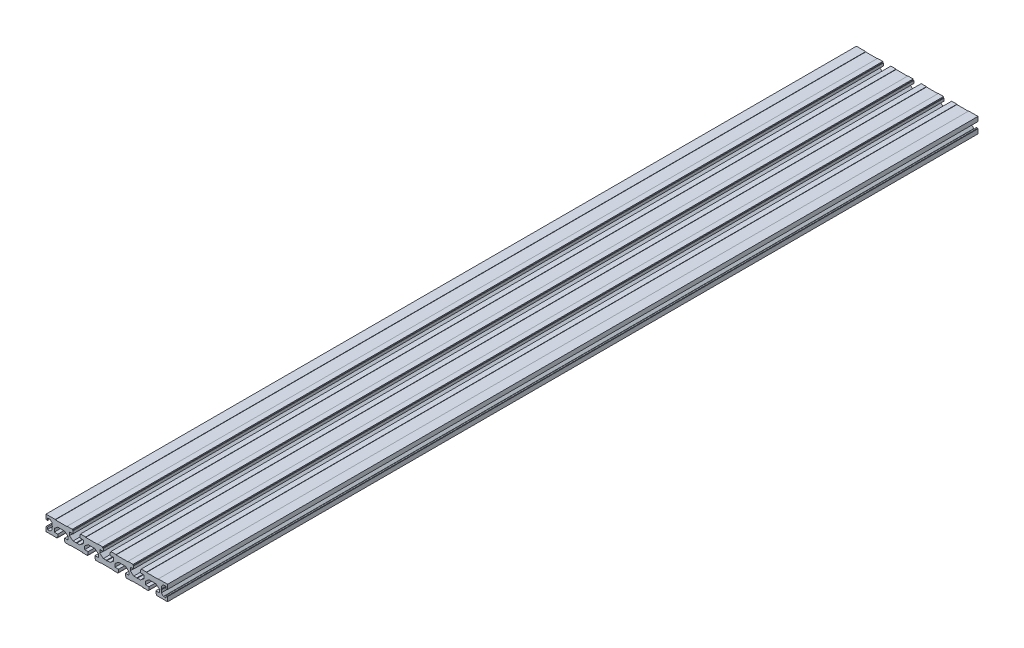
SolidWorks part; units mm, degrees
ref_plane "Front Plane" through (0, 0, 0) normal (0, 0, 1) x (1, 0, 0)
ref_plane "Top Plane" through (0, 0, 0) normal (0, 1, 0) x (1, 0, 0)
ref_plane "Right Plane" through (0, 0, 0) normal (1, 0, 0) x (0, 0, -1)
sketch "Model" plane through (0, 0, 0) normal (0, 0, 1) x (1, 0, 0)
  line L0 (-16.5, -11.25) -> (-16.5, -9.75)
  line L1 (-16.5, -9.75) -> (-17.4, -9.75)
  line L2 (-17.4, -9.75) -> (-17.4, -5.75)
  line L3 (-17.4, -5.75) -> (-12.25, -5.75)
  line L4 (-12.25, -5.75) -> (-12.25, -0.9799)
  line L5 (-12.25, -0.9799) -> (-17.5, 3.25)
  line L6 (-17.5, 3.25) -> (-22, 3.25)
  line L7 (-22, 3.25) -> (-22.5, 3.75)
  line L8 (-22.5, 3.75) -> (-23, 3.25)
  line L9 (-23, 3.25) -> (-27.5, 3.25)
  line L10 (-27.5, 3.25) -> (-32.75, -0.9799)
  line L11 (-32.75, -0.9799) -> (-32.75, -5.75)
  line L12 (-32.75, -5.75) -> (-27.6, -5.75)
  line L13 (-27.6, -5.75) -> (-27.6, -9.75)
  line L14 (-27.6, -9.75) -> (-28.5, -9.75)
  line L15 (-28.5, -11.25) -> (-28.5, -9.75)
  line L16 (-36.25, -11.25) -> (-36.25, -10.75)
  line L17 (-36.25, -10.75) -> (-53.75, -10.75)
  line L18 (-53.75, -11.25) -> (-53.75, -10.75)
  line L19 (-61.5, -11.25) -> (-61.5, -9.75)
  line L20 (-61.5, -9.75) -> (-62.4, -9.75)
  line L21 (-62.4, -9.75) -> (-62.4, -5.75)
  line L22 (-62.4, -5.75) -> (-57.25, -5.75)
  line L23 (-57.25, -5.75) -> (-57.25, -0.9799)
  line L24 (-57.25, -0.9799) -> (-62.5, 3.25)
  line L25 (-62.5, 3.25) -> (-67, 3.25)
  line L26 (-67, 3.25) -> (-67.5, 3.75)
  line L27 (-67.5, 3.75) -> (-68, 3.25)
  line L28 (-68, 3.25) -> (-72.5, 3.25)
  line L29 (-72.5, 3.25) -> (-77.75, -0.9799)
  line L30 (-77.75, -0.9799) -> (-77.75, -5.75)
  line L31 (-77.75, -5.75) -> (-72.6, -5.75)
  line L32 (-72.6, -5.75) -> (-72.6, -9.75)
  line L33 (-72.6, -9.75) -> (-73.5, -9.75)
  line L34 (-73.5, -11.25) -> (-73.5, -9.75)
  line L35 (-90, -4.6) -> (-89.5, -4.1)
  line L36 (-89.5, -4.1) -> (-87.8, -4.1)
  line L37 (-87.8, -4.1) -> (-87.8, -7.456)
  line L38 (-87.8, -7.456) -> (-83.8702, -7.456)
  line L39 (-83.8702, -7.456) -> (-80.75, -4.3358)
  line L40 (-80.75, -4.3358) -> (-80.75, -0.5)
  line L41 (-80.75, -0.5) -> (-80.25, 0)
  line L42 (-80.25, 0) -> (-80.75, 0.5)
  line L43 (-80.75, 0.5) -> (-80.75, 4.3358)
  line L44 (-80.75, 4.3358) -> (-83.8702, 7.456)
  line L45 (-83.8702, 7.456) -> (-87.8, 7.456)
  line L46 (-87.8, 7.456) -> (-87.8, 4.1)
  line L47 (-87.8, 4.1) -> (-89.5, 4.1)
  line L48 (-76.25, 11.25) -> (-90, 11.25)
  line L49 (-76.25, 11.25) -> (-76.25, 10.75)
  line L50 (-76.25, 10.75) -> (-58.75, 10.75)
  line L51 (-58.75, 11.25) -> (-58.75, 10.75)
  line L52 (-51, 11.25) -> (-58.75, 11.25)
  line L53 (-51, 11.25) -> (-51, 9.75)
  line L54 (-51, 9.75) -> (-50.1, 9.75)
  line L55 (-50.1, 9.75) -> (-50.1, 5.75)
  line L56 (-50.1, 5.75) -> (-55.25, 5.75)
  line L57 (-55.25, 5.75) -> (-55.25, 0.9799)
  line L58 (-55.25, 0.9799) -> (-50, -3.25)
  line L59 (-50, -3.25) -> (-45.5, -3.25)
  line L60 (-45.5, -3.25) -> (-45, -3.75)
  line L61 (-45, -3.75) -> (-44.5, -3.25)
  line L62 (-44.5, -3.25) -> (-40, -3.25)
  line L63 (-40, -3.25) -> (-34.75, 0.9799)
  line L64 (-34.75, 0.9799) -> (-34.75, 5.75)
  line L65 (-34.75, 5.75) -> (-39.9, 5.75)
  line L66 (-39.9, 5.75) -> (-39.9, 9.75)
  line L67 (-39.9, 9.75) -> (-39, 9.75)
  line L68 (-39, 11.25) -> (-39, 9.75)
  line L69 (-31.25, 11.25) -> (-39, 11.25)
  line L70 (-31.25, 11.25) -> (-31.25, 10.75)
  line L71 (-31.25, 10.75) -> (-13.75, 10.75)
  line L72 (-13.75, 11.25) -> (-13.75, 10.75)
  line L73 (-6, 11.25) -> (-13.75, 11.25)
  line L74 (-6, 11.25) -> (-6, 9.75)
  line L75 (-6, 9.75) -> (-5.1, 9.75)
  line L76 (-5.1, 9.75) -> (-5.1, 5.75)
  line L77 (-5.1, 5.75) -> (-10.25, 5.75)
  line L78 (-10.25, 5.75) -> (-10.25, 0.9799)
  line L79 (-10.25, 0.9799) -> (-5, -3.25)
  line L80 (-5, -3.25) -> (-0.5, -3.25)
  line L81 (-0.5, -3.25) -> (0, -3.75)
  line L82 (0, -3.75) -> (0.5, -3.25)
  line L83 (0.5, -3.25) -> (5, -3.25)
  line L84 (5, -3.25) -> (10.25, 0.9799)
  line L85 (10.25, 0.9799) -> (10.25, 5.75)
  line L86 (10.25, 5.75) -> (5.1, 5.75)
  line L87 (5.1, 5.75) -> (5.1, 9.75)
  line L88 (5.1, 9.75) -> (6, 9.75)
  line L89 (6, 11.25) -> (6, 9.75)
  line L90 (13.75, 11.25) -> (6, 11.25)
  line L91 (13.75, 11.25) -> (13.75, 10.75)
  line L92 (13.75, 10.75) -> (31.25, 10.75)
  line L93 (31.25, 11.25) -> (31.25, 10.75)
  line L94 (39, 11.25) -> (31.25, 11.25)
  line L95 (39, 9.75) -> (39.9, 9.75)
  line L96 (39.9, 9.75) -> (39.9, 5.75)
  line L97 (39.9, 5.75) -> (34.75, 5.75)
  line L98 (34.75, 5.75) -> (34.75, 0.9799)
  line L99 (34.75, 0.9799) -> (40, -3.25)
  line L100 (40, -3.25) -> (44.5, -3.25)
  line L101 (44.5, -3.25) -> (45, -3.75)
  line L102 (45, -3.75) -> (45.5, -3.25)
  line L103 (45.5, -3.25) -> (50, -3.25)
  line L104 (50, -3.25) -> (55.25, 0.9799)
  line L105 (55.25, 0.9799) -> (55.25, 5.75)
  line L106 (55.25, 5.75) -> (50.1, 5.75)
  line L107 (50.1, 5.75) -> (50.1, 9.75)
  line L108 (50.1, 9.75) -> (51, 9.75)
  line L109 (51, 11.25) -> (51, 9.75)
  line L110 (58.75, 11.25) -> (51, 11.25)
  line L111 (58.75, 11.25) -> (58.75, 10.75)
  line L112 (58.75, 10.75) -> (76.25, 10.75)
  line L113 (76.25, 11.25) -> (76.25, 10.75)
  line L114 (90, 11.25) -> (76.25, 11.25)
  line L115 (90, 4.6) -> (90, 11.25)
  line L116 (90, 4.6) -> (89.5, 4.1)
  line L117 (89.5, 4.1) -> (87.8, 4.1)
  line L118 (87.8, 4.1) -> (87.8, 7.456)
  line L119 (87.8, 7.456) -> (83.8702, 7.456)
  line L120 (83.8702, 7.456) -> (80.75, 4.3358)
  line L121 (80.75, 4.3358) -> (80.75, 0.5)
  line L122 (80.75, 0.5) -> (80.25, 0)
  line L123 (80.25, 0) -> (80.75, -0.5)
  line L124 (80.75, -0.5) -> (80.75, -4.3358)
  line L125 (80.75, -4.3358) -> (83.8702, -7.456)
  line L126 (83.8702, -7.456) -> (87.8, -7.456)
  line L127 (87.8, -7.456) -> (87.8, -4.1)
  line L128 (87.8, -4.1) -> (89.5, -4.1)
  line L129 (89.5, -4.1) -> (90, -4.6)
  line L130 (90, -11.25) -> (90, -4.6)
  line L131 (73.5, -11.25) -> (73.5, -9.75)
  line L132 (73.5, -9.75) -> (72.6, -9.75)
  line L133 (72.6, -9.75) -> (72.6, -5.75)
  line L134 (72.6, -5.75) -> (77.75, -5.75)
  line L135 (77.75, -5.75) -> (77.75, -0.9799)
  line L136 (77.75, -0.9799) -> (72.5, 3.25)
  line L137 (72.5, 3.25) -> (68, 3.25)
  line L138 (68, 3.25) -> (67.5, 3.75)
  line L139 (67.5, 3.75) -> (67, 3.25)
  line L140 (67, 3.25) -> (62.5, 3.25)
  line L141 (62.5, 3.25) -> (57.25, -0.9799)
  line L142 (57.25, -0.9799) -> (57.25, -5.75)
  line L143 (57.25, -5.75) -> (62.4, -5.75)
  line L144 (62.4, -5.75) -> (62.4, -9.75)
  line L145 (62.4, -9.75) -> (61.5, -9.75)
  line L146 (61.5, -11.25) -> (61.5, -9.75)
  line L147 (53.75, -11.25) -> (53.75, -10.75)
  line L148 (53.75, -10.75) -> (36.25, -10.75)
  line L149 (36.25, -11.25) -> (36.25, -10.75)
  line L150 (28.5, -11.25) -> (28.5, -9.75)
  line L151 (28.5, -9.75) -> (27.6, -9.75)
  line L152 (27.6, -9.75) -> (27.6, -5.75)
  line L153 (27.6, -5.75) -> (32.75, -5.75)
  line L154 (32.75, -5.75) -> (32.75, -0.9799)
  line L155 (32.75, -0.9799) -> (27.5, 3.25)
  line L156 (27.5, 3.25) -> (23, 3.25)
  line L157 (23, 3.25) -> (22.5, 3.75)
  line L158 (22.5, 3.75) -> (22, 3.25)
  line L159 (22, 3.25) -> (17.5, 3.25)
  line L160 (17.5, 3.25) -> (12.25, -0.9799)
  line L161 (12.25, -0.9799) -> (12.25, -5.75)
  line L162 (12.25, -5.75) -> (17.4, -5.75)
  line L163 (17.4, -5.75) -> (17.4, -9.75)
  line L164 (17.4, -9.75) -> (16.5, -9.75)
  line L165 (16.5, -11.25) -> (16.5, -9.75)
  line L166 (-89.5, 4.1) -> (-90, 4.6)
  line L167 (-90, -4.6) -> (-90, -11.25)
  line L168 (-90, 11.25) -> (-90, 4.6)
  line L169 (28.5, -11.25) -> (36.25, -11.25)
  line L170 (53.75, -11.25) -> (61.5, -11.25)
  line L171 (-61.5, -11.25) -> (-53.75, -11.25)
  line L172 (-36.25, -11.25) -> (-28.5, -11.25)
  line L173 (-16.5, -11.25) -> (-8.75, -11.25)
  line L174 (8.75, -11.25) -> (16.5, -11.25)
  line L175 (73.5, -11.25) -> (90, -11.25)
  line L176 (-90, -11.25) -> (-73.5, -11.25)
  line L177 (-8.75, -11.25) -> (-8.75, -10.75)
  line L178 (8.75, -10.75) -> (-8.75, -10.75)
  line L179 (8.75, -11.25) -> (8.75, -10.75)
  line L180 (39, 11.25) -> (39, 9.75)
extrude "Boss-Extrude1" add sketch "Model" along normal blind 1200
equation "\"e_extrude_22.5_180\"= 1200"
equation "\"D1@Boss-Extrude1\"=\"e_extrude_22.5_180\""
